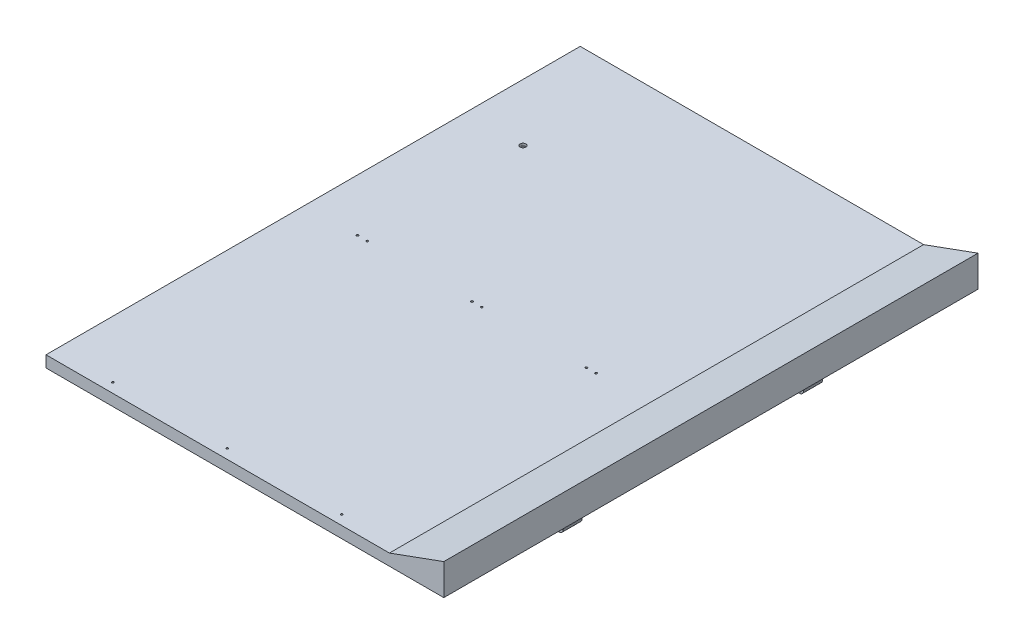
SolidWorks part; units mm, degrees
ref_plane "Front Plane" through (0, 0, 0) normal (0, 0, 1) x (1, 0, 0)
ref_plane "Top Plane" through (0, 0, 0) normal (0, 1, 0) x (1, 0, 0)
ref_plane "Right Plane" through (0, 0, 0) normal (1, 0, 0) x (0, 0, -1)
sketch "Sketch2" plane through (0, 0, 0) normal (0, 0, 1) x (1, 0, 0)
  line L0 (0, 0) -> (0, 81.8658)
  line L1 (0, 81.8658) -> (-142.5, 30)
  line L2 (-142.5, 30) -> (-1042.5, 30)
  line L5 (0, 0) -> (-1042.5, 0)
  line L6 (-1042.5, 0) -> (-1042.5, 30)
  dimension "D1" = 30
  dimension "D2" = 160
  dimension "D3" = 1042.5
  dimension "D4" = 900
extrude "Boss-Extrude1" add sketch "Sketch2" along normal blind 1100 and the other way blind 300
sketch "Sketch3" plane through (0, 0, 0) normal (0, 0, 1) x (1, 0, 0)
  line L0 (-47.5, 0) -> (-47.5, -50)
  line L1 (-1042.5, 0) -> (0, 0) construction
  line L2 (-57.5, -60) -> (-512.5, -60)
  line L3 (-522.5, -50) -> (-522.5, 0)
  line L4 (-522.5, 0) -> (-47.5, 0)
  line L5 (-510, -50) -> (-60, -50) construction
  line L6 (-510, -42.5) -> (-60, -42.5)
  line L7 (-510, -57.5) -> (-60, -57.5)
  line L8 (0, 0) -> (0, 81.8658) construction
  line L9 (-1022.5, 0) -> (-1022.5, -50)
  line L10 (-1012.5, -60) -> (-1007.5, -60)
  line L11 (-997.5, -50) -> (-997.5, 0)
  line L12 (-997.5, 0) -> (-1022.5, 0)
  arc A0 (-510, -42.5) -> (-510, -57.5) centre (-510, -50) ccw
  arc A1 (-60, -57.5) -> (-60, -42.5) centre (-60, -50) ccw
  arc A2 (-512.5, -60) -> (-522.5, -50) centre (-512.5, -50) cw
  arc A3 (-47.5, -50) -> (-57.5, -60) centre (-57.5, -50) cw
  circle A6 centre (-1010, -50) radius 7.5
  arc A7 (-1007.5, -60) -> (-997.5, -50) centre (-1007.5, -50) ccw
  arc A8 (-1022.5, -50) -> (-1012.5, -60) centre (-1012.5, -50) ccw
  point P8 (-285, -50)
  point P17 (-522.5, -60)
  point P20 (-47.5, -60)
  point P29 (-997.5, -60)
  point P32 (-1022.5, -60)
  dimension "D4" = 12.5
  dimension "D5" = 60
  dimension "D7" = 7.5
  dimension "D8" = 10
  dimension "D10" = 50
  dimension "D11" = 15
  dimension "D12" = 10
  dimension "D13" = 12.5
  dimension "D14" = 500
  dimension "D1" = 60
  dimension "D2" = 475
  dimension "D3" = 50
  dimension "D6" = 450
  dimension "D9" = 25
  dimension "D15" = 60
extrude "Boss-Extrude2" add sketch "Sketch3" along normal blind 800
sketch "Sketch5" plane through (0, 30, 0) normal (0, 1, 0) x (1, 0, 0)
  line L0 (-1042.5, -1100) -> (-142.5, -1100) construction
  line L1 (-142.5, -1100) -> (-142.5, 300) construction
  circle A0 centre (-892.5, 0) radius 7.5
  dimension "D1" = 15
  dimension "D2" = 1100
  dimension "D3" = 750
extrude "Cut-Extrude2" cut sketch "Sketch5" against normal through all
sketch "Sketch9" plane through (-47.5, 0, 0) normal (1, 0, 0) x (0, 0, -1)
  line L0 (-690, 0) -> (-690, -60)
  line L1 (300, 0) -> (-1100, 0) construction
  line L2 (-800, -60) -> (0, -60) construction
  line L3 (-690, -60) -> (-110, -60)
  line L4 (-110, -60) -> (-110, 0)
  line L5 (-800, 0) -> (0, 0) construction
  line L6 (-110, 0) -> (-690, 0)
  line L7 (-740, -50) -> (-740, -60)
  line L8 (-740, -60) -> (-800, -60)
  line L9 (0, -50) -> (0, 0) construction
  line L10 (-800, -60) -> (-800, -50)
  line L12 (-800, -50) -> (0, -50) construction
  line L13 (0, 0) -> (0, -60)
  line L14 (0, -60) -> (-60, -60)
  line L15 (-740, -50) -> (-740, 0)
  line L16 (-740, 0) -> (-800, 0)
  line L17 (-800, -50) -> (-800, 0) construction
  line L18 (-800, 0) -> (-800, -50)
  line L19 (-60, -60) -> (-60, 0)
  line L20 (-60, 0) -> (0, 0)
  dimension "D1" = 580
  dimension "D2" = 110
  dimension "D3" = 60
  dimension "D4" = 50
  dimension "D5" = 60
  dimension "5" = 50
extrude "Cut-Extrude5" cut sketch "Sketch9" against normal through all
sketch "Sketch6" plane through (0, 0, 0) normal (0, -1, 0) x (1, 0, 0)
  line L1 (-905, 16) -> (-880, 16)
  line L2 (-905, 16) -> (-905, -16)
  line L3 (-905, -16) -> (-880, -16)
  line L4 (-880, 16) -> (-880, -16)
  line L5 (-905, 16) -> (-880, -16) construction
  line L6 (-905, -16) -> (-880, 16) construction
  point P0 (-892.5, 0)
  dimension "D1" = 32
  dimension "D2" = 25
extrude "Boss-Extrude3" add sketch "Sketch6" along normal blind 37.5
sketch "Sketch7" plane through (0, 0, 16) normal (0, 0, 1) x (1, 0, 0)
  line L0 (-880, 0) -> (-905, 0) construction
  line L1 (-900.5, 0) -> (-884.5, 0)
  line L2 (-900.5, 0) -> (-900.5, -32.5)
  line L3 (-900.5, -32.5) -> (-884.5, -32.5)
  line L4 (-884.5, 0) -> (-884.5, -32.5)
  line L5 (-905, -37.5) -> (-905, 0) construction
  dimension "D1" = 4.5
  dimension "D2" = 16
  dimension "D3" = 32.5
extrude "Cut-Extrude3" cut sketch "Sketch7" against normal through all
sketch "Sketch8" plane through (0, 0, 0) normal (0, -1, 0) x (1, 0, 0)
  line L0 (-900.5, -16) -> (-900.5, 16) construction
  line L1 (-900.5, -32) -> (-884.5, -32)
  line L2 (-900.5, -32) -> (-900.5, 32)
  line L3 (-900.5, 32) -> (-884.5, 32)
  line L4 (-884.5, -32) -> (-884.5, 32)
  line L5 (-900.5, -32) -> (-884.5, 32) construction
  line L6 (-900.5, 32) -> (-884.5, -32) construction
  point P0 (-892.5, 0)
  dimension "D1" = 0
  dimension "D2" = 64
extrude "Cut-Extrude4" cut sketch "Sketch8" against normal blind 24
sketch "Sketch10" plane through (0, 30, 0) normal (0, 1, 0) x (1, 0, 0)
  line L0 (-1042.5, -375) -> (-142.5, -375) construction
  line L1 (-1042.5, 300) -> (-1042.5, -1100) construction
  line L2 (-142.5, 300) -> (-142.5, -1100) construction
  line L3 (-892.5, -375) -> (-892.5, 300) construction
  line L4 (-142.5, 300) -> (-1042.5, 300) construction
  line L5 (-592.5, -375) -> (-592.5, 300) construction
  line L6 (-292.5, -375) -> (-292.5, 300) construction
  line L8 (-892.5, -1075) -> (-292.5, -1075) construction
  line L9 (-905.2, -420.95) -> (-879.8, -420.95) construction
  line L10 (-879.8, -420.95) -> (-605.2, -420.95) construction
  line L11 (-605.2, -420.95) -> (-579.8, -420.95) construction
  line L12 (-579.8, -420.95) -> (-413.5459, -420.95) construction
  line L13 (-413.5459, -420.95) -> (-279.8, -420.95) construction
  circle A0 centre (-892.5, -1075) radius 2.5908
  circle A1 centre (-592.5, -1075) radius 2.5908
  circle A2 centre (-292.5, -1075) radius 2.5908
  circle A3 centre (-905.2, -420.95) radius 2.5908
  circle A4 centre (-879.8, -420.95) radius 2.5908
  circle A5 centre (-605.2, -420.95) radius 2.5908
  circle A6 centre (-579.8, -420.95) radius 2.5908
  circle A7 centre (-305.2, -420.95) radius 2.5908
  circle A8 centre (-279.8, -420.95) radius 2.5908
  dimension "D6" = 5.1816
  dimension "D7" = 5.1816
  dimension "D8" = 12.7
  dimension "D10" = 5.1816
  dimension "D11" = 5.1816
  dimension "D13" = 25.4
  dimension "D14" = 5.1816
  dimension "D15" = 5.1816
  dimension "D17" = 25.4
  dimension "D18" = 5.1816
  dimension "D19" = 5.1816
  dimension "D20" = 5.1816
  dimension "D22" = 654.05
  dimension "D21" = 700
  dimension "D1" = 150
  dimension "D2" = 300
  dimension "D3" = 300
  dimension "D4" = 700
  dimension "D5" = 675
  dimension "D9" = 25.4
  dimension "D12" = 12.7
  dimension "D16" = 12.7
extrude "Cut-Extrude6" cut sketch "Sketch10" against normal blind 20
